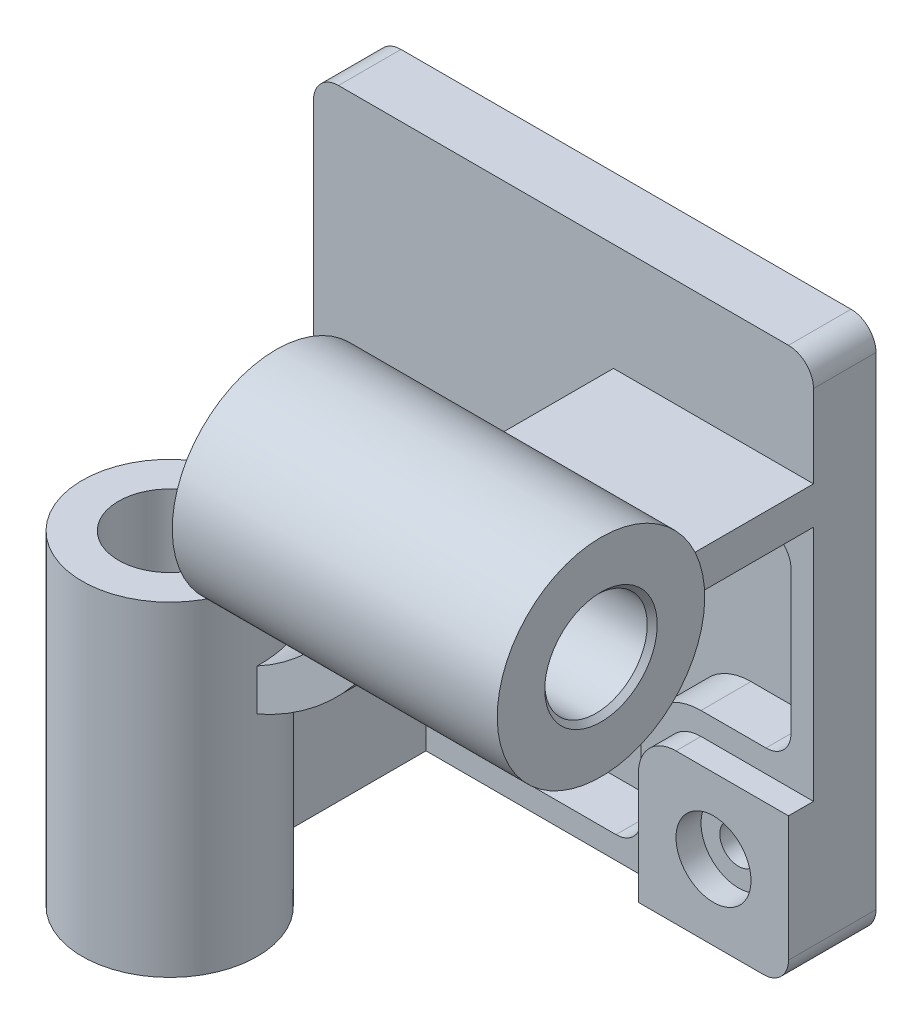
SolidWorks part; units mm, degrees
ref_plane "Front Plane" through (0, 0, 0) normal (0, 0, 1) x (1, 0, 0)
ref_plane "Top Plane" through (0, 0, 0) normal (0, 1, 0) x (1, 0, 0)
ref_plane "Right Plane" through (0, 0, 0) normal (1, 0, 0) x (0, 0, -1)
sketch "Sketch1" plane through (0, 0, 0) normal (0, 0, 1) x (1, 0, 0)
  line L0 (-100.4975, 0) -> (108.9552, 0) construction
  line L1 (0, 89.5522) -> (0, -74.6269) construction
  line L3 (-100, 106.5) -> (100, 106.5)
  line L4 (-100, 106.5) -> (-100, -106.5)
  line L5 (-100, -106.5) -> (100, -106.5)
  line L6 (100, 106.5) -> (100, -106.5)
  line L7 (-100, 106.5) -> (100, -106.5) construction
  line L8 (-100, -106.5) -> (100, 106.5) construction
  point P5 (0, 0)
  dimension "D1" = 200
  dimension "D2" = 213
extrude "Boss-Extrude1" add sketch "Sketch1" along normal blind 25
sketch "Sketch3" plane through (0, 0, 25) normal (0, 0, 1) x (1, 0, 0)
  line L5 (100, -106.5) -> (40, -106.5)
  line L6 (100, -106.5) -> (100, -46.5)
  line L7 (100, -46.5) -> (55, -46.5)
  line L8 (40, -106.5) -> (40, -61.5)
  arc A0 (55, -46.5) -> (40, -61.5) centre (55, -61.5) ccw
  point P6 (40, -46.5)
  dimension "D3" = 15
  dimension "D1" = 60
  dimension "D2" = 60
extrude "Boss-Extrude2" add sketch "Sketch3" along normal blind 10
fillet "Fillet1" radius 10 4 edges at (100, -106.5, 17.5) (100, 106.5, 12.5) (-100, 106.5, 12.5) (-100, -106.5, 12.5)
sketch "Sketch4" plane through (0, 0, 25) normal (0, 0, 1) x (1, 0, 0)
  line L0 (100, 63.5) -> (-100, 63.5) construction
  line L1 (100, -46.5) -> (100, 96.5) construction
  line L2 (-100, 96.5) -> (-100, -96.5) construction
  line L3 (-70, -106.5) -> (-70, 106.5) construction
  line L4 (-90, -106.5) -> (40, -106.5) construction
  line L5 (90, 106.5) -> (-90, 106.5) construction
  line L6 (100, -96.5) -> (100, -46.5) construction
  line L7 (40, -106.5) -> (90, -106.5) construction
  line L8 (100, 63.5) -> (20, 63.5)
  line L9 (-70, -106.5) -> (-70, -26.5)
  line L10 (-55, -106.5) -> (-55, -40.423)
  line L11 (100, 48.5) -> (33.923, 48.5)
  arc A0 (-70, -26.5) -> (20, 63.5) centre (-70, 63.5) ccw
  arc A1 (-55, -40.423) -> (33.923, 48.5) centre (-70, 63.5) ccw
  dimension "D5" = 90
  dimension "D1" = 170
  dimension "D2" = 170
  dimension "D3" = 80
  dimension "D4" = 80
  dimension "D6" = 15
extrude "Extrude-Thin1" add sketch "Sketch4" along normal blind 95 thin thin type one direction wall 10
sketch "Sketch5" plane through (0, -106.5, 0) normal (0, -1, 0) x (1, 0, 0)
  line L0 (-55, 120) -> (-70, 120) construction
  circle A0 centre (-62.5, 120) radius 35
  dimension "D1" = 70
extrude "Boss-Extrude3" add sketch "Sketch5" along normal blind 10 and the other way blind 120
sketch "Sketch6" plane through (100, 0, 0) normal (1, 0, 0) x (0, 0, -1)
  line L0 (-120, 63.5) -> (-120, 48.5) construction
  circle A0 centre (-120, 56) radius 41.5
  dimension "D1" = 83
extrude "Boss-Extrude4" add sketch "Sketch6" along normal blind 10 and the other way blind 120
sketch "Sketch7" plane through (0, -116.5, 0) normal (0, -1, 0) x (1, 0, 0)
  circle A0 centre (-62.5, 120) radius 20.5
  dimension "D1" = 41
extrude "Cut-Extrude1" cut sketch "Sketch7" against normal up to next
sketch "Sketch8" plane through (110, 0, 0) normal (1, 0, 0) x (0, 0, -1)
  circle A0 centre (-120, 56) radius 20.5
  dimension "D1" = 41
extrude "Cut-Extrude2" cut sketch "Sketch8" against normal up to next
chamfer "Chamfer1" distance 2 angle 45 2 edges at (-62.5, -116.5, 99.5) (110, 76.5, 120)
sketch "Sketch9" plane through (0, 0, 25) normal (0, 0, 1) x (1, 0, 0)
  line L18 (-46, -47.9451) -> (-46, -97.5)
  line L19 (-46, -97.5) -> (31, -97.5)
  line L20 (31, -97.5) -> (31, -61.5)
  line L21 (55, -37.5) -> (91, -37.5)
  line L22 (91, -37.5) -> (91, 39.5)
  line L23 (91, 39.5) -> (41.4451, 39.5)
  line L24 (-46, -55.7476) -> (-46, -87.5)
  line L25 (-36, -97.5) -> (21, -97.5)
  line L26 (31, -87.5) -> (31, -61.5)
  line L27 (55, -37.5) -> (81, -37.5)
  line L28 (91, -27.5) -> (91, 29.5)
  line L29 (81, 39.5) -> (49.2476, 39.5)
  arc A4 (21, -97.5) -> (31, -87.5) centre (21, -87.5) ccw
  arc A5 (49.2476, 39.5) -> (39.6309, 32.2419) centre (49.2476, 29.5) ccw
  arc A6 (55, -37.5) -> (31, -61.5) centre (55, -61.5) ccw
  arc A7 (-46, -47.9451) -> (41.4451, 39.5) centre (-70, 63.5) ccw
  arc A8 (55, -37.5) -> (31, -61.5) centre (55, -61.5) ccw
  arc A9 (-38.7419, -46.1309) -> (39.6309, 32.2419) centre (-70, 63.5) ccw
  arc A10 (91, 29.5) -> (81, 39.5) centre (81, 29.5) ccw
  arc A11 (81, -37.5) -> (91, -27.5) centre (81, -27.5) ccw
  arc A12 (-46, -87.5) -> (-36, -97.5) centre (-36, -87.5) ccw
  arc A13 (-46, -55.7476) -> (-38.7419, -46.1309) centre (-36, -55.7476) cw
  dimension "D2" = 10
  dimension "D1" = 9
extrude "Cut-Extrude3" cut sketch "Sketch9" against normal blind 20
hole_wizard "CBORE for M8 Hex Head Bolt1" positions "Sketch10" profile "Sketch11" counterbore size "M8" standard "ANSI Metric" end condition through all
sketch "Sketch10" plane through (0, 0, 35) normal (0, 0, 1) x (1, 0, 0)
  line L0 (100, -96.5) -> (100, -46.5) construction
  line L1 (40, -106.5) -> (90, -106.5) construction
  point P0 (70, -76.5)
  dimension "D1" = 30
  dimension "D2" = 30
sketch "Sketch11" plane through (70, -76.5, 35) normal (1, 0, 0) x (0, -1, 0)
  line L0 (0, 0) -> (0, 35)
  line L1 (0, 35) -> (7.5, 35)
  line L3 (7.5, 35) -> (7.5, 10)
  line L4 (7.5, 10) -> (15, 10)
  line L5 (15, 10) -> (15, 0)
  line L7 (15, 0) -> (0, 0)
  line L11 (0, -6.35) -> (0, 107.95) construction
  dimension "Thru Hole Dia." = 15
  dimension "Thru Hole Depth" = 35
  dimension "C'Bore Dia." = 30
  dimension "C'Bore Depth" = 10
